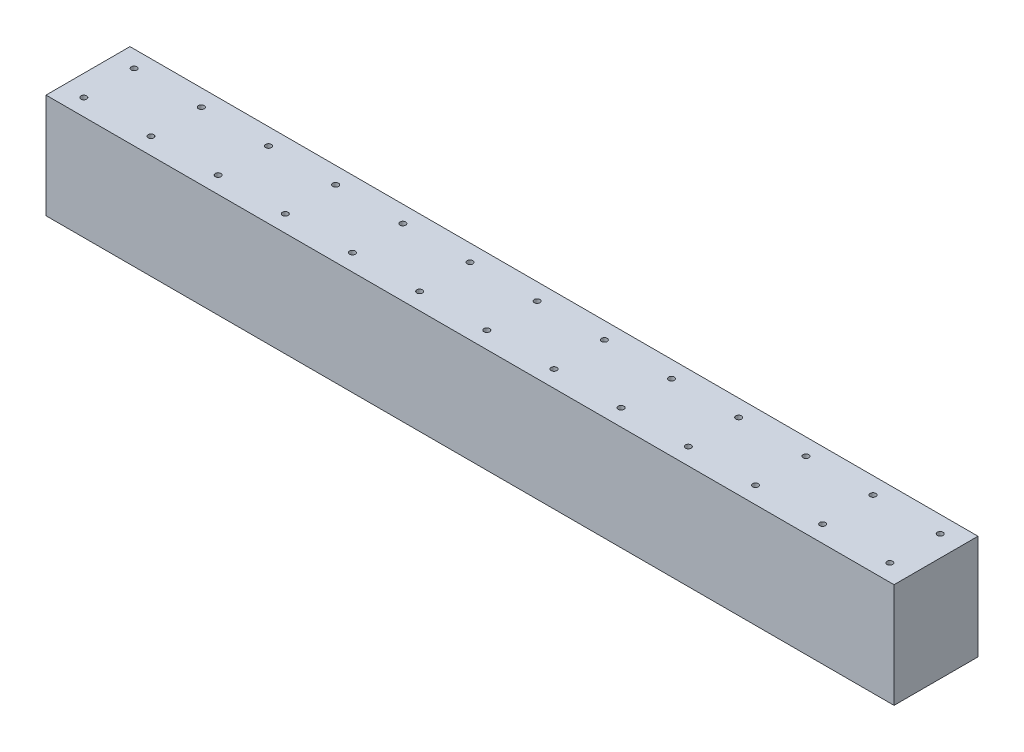
SolidWorks part; units mm, degrees
material "Plain Carbon Steel"
ref_plane "Front Plane" through (0, 0, 0) normal (0, 0, 1) x (1, 0, 0)
ref_plane "Top Plane" through (0, 0, 0) normal (0, 1, 0) x (1, 0, 0)
ref_plane "Right Plane" through (0, 0, 0) normal (1, 0, 0) x (0, 0, -1)
sketch "Sketch1" plane through (0, 0, 0) normal (1, 0, 0) x (0, 0, -1)
  line L1 (-50, -62.25) -> (50, -62.25)
  line L2 (-50, -62.25) -> (-50, 62.25)
  line L3 (-50, 62.25) -> (50, 62.25)
  line L4 (50, -62.25) -> (50, 62.25)
  line L5 (-50, -62.25) -> (50, 62.25) construction
  line L6 (-50, 62.25) -> (50, -62.25) construction
  point P0 (0, 0)
  dimension "D1" = 100
  dimension "D2" = 124.5
extrude "Boss-Extrude1" add sketch "Sketch1" along normal mid plane 1010
hole_wizard "M8 Tapped Hole1" positions "Sketch4" profile "Sketch3" tap size "M8" standard "ISO"
sketch "Sketch4" plane through (0, 62.25, 0) normal (0, 1, 0) x (1, 0, 0)
  point P0 (480, 30)
  point P3 (480, -30)
  point P6 (400, 30)
  point P9 (400, -30)
  point P12 (320, 30)
  point P15 (320, -30)
  point P18 (240, -30)
  point P21 (240, 30)
  point P24 (160, 30)
  point P27 (160, -30)
  point P30 (80, 30)
  point P33 (80, -30)
  point P36 (0, -30)
  point P39 (0, 30)
  point P42 (-80, -30)
  point P45 (-80, 30)
  point P48 (-160, -30)
  point P51 (-160, 30)
  point P54 (-240, -30)
  point P57 (-240, 30)
  point P60 (-320, -30)
  point P63 (-320, 30)
  point P66 (-400, -30)
  point P69 (-400, 30)
  point P72 (-480, 30)
  point P75 (-480, -30)
sketch "Sketch3" plane through (480, 62.25, -30) normal (1, 0, 0) x (0, 0, 1)
  line L0 (0, 0) -> (0, 24.2929)
  line L1 (0, 24.2929) -> (3.4, 22.25)
  line L2 (3.4, 22.25) -> (3.4, 0)
  line L5 (3.4, 0) -> (0, 0)
  line L10 (0, 24.2929) -> (-3.4, 22.25) construction
  line L11 (0, -6.35) -> (0, 107.95) construction
  dimension "Tap Drill Dia." = 6.8
  dimension "Tap Drill Depth" = 22.25
  dimension "Drill Angle" = 118
cosmetic thread "Hole Thread1"
cosmetic thread "Hole Thread2"
cosmetic thread "Hole Thread3"
cosmetic thread "Hole Thread4"
cosmetic thread "Hole Thread5"
cosmetic thread "Hole Thread6"
cosmetic thread "Hole Thread7"
cosmetic thread "Hole Thread8"
cosmetic thread "Hole Thread9"
cosmetic thread "Hole Thread10"
cosmetic thread "Hole Thread11"
cosmetic thread "Hole Thread12"
cosmetic thread "Hole Thread13"
cosmetic thread "Hole Thread14"
cosmetic thread "Hole Thread15"
cosmetic thread "Hole Thread16"
cosmetic thread "Hole Thread17"
cosmetic thread "Hole Thread18"
cosmetic thread "Hole Thread19"
cosmetic thread "Hole Thread20"
cosmetic thread "Hole Thread21"
cosmetic thread "Hole Thread22"
cosmetic thread "Hole Thread23"
cosmetic thread "Hole Thread24"
cosmetic thread "Hole Thread25"
cosmetic thread "Hole Thread26"
